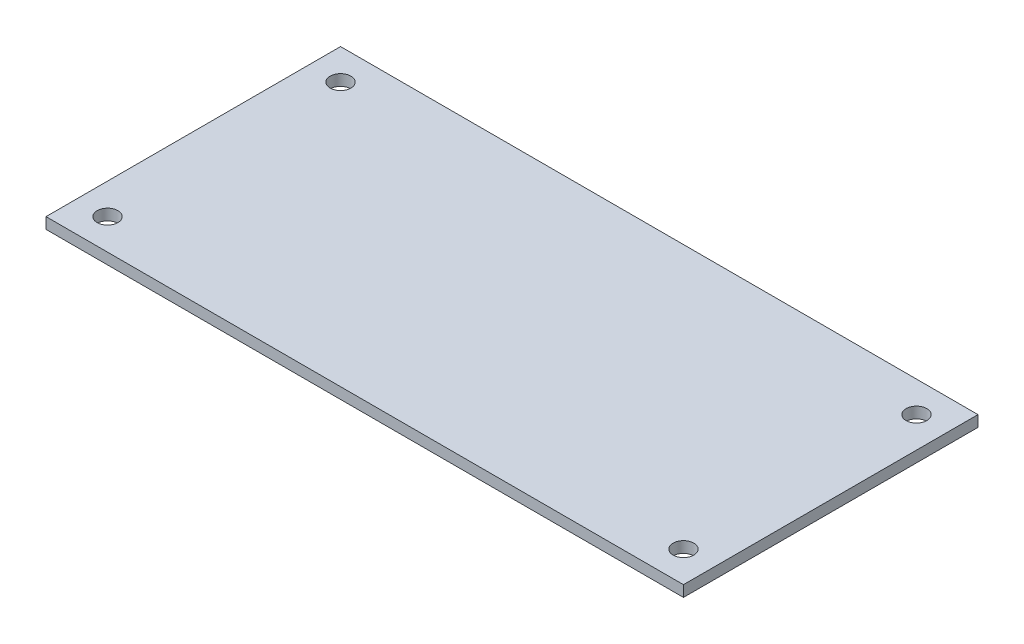
SolidWorks part; units mm, degrees
ref_plane "Front" through (0, 0, 0) normal (0, 0, 1) x (1, 0, 0)
ref_plane "Top" through (0, 0, 0) normal (0, 1, 0) x (1, 0, 0)
ref_plane "Right" through (0, 0, 0) normal (1, 0, 0) x (0, 0, -1)
sketch "Sketch2" plane through (0, 0, 0) normal (0, 1, 0) x (1, 0, 0)
  line L1 (-46.0375, 21.2725) -> (46.0375, 21.2725)
  line L2 (-46.0375, 21.2725) -> (-46.0375, -21.2725)
  line L3 (-46.0375, -21.2725) -> (46.0375, -21.2725)
  line L4 (46.0375, 21.2725) -> (46.0375, -21.2725)
  line L5 (-46.0375, 21.2725) -> (46.0375, -21.2725) construction
  line L6 (-46.0375, -21.2725) -> (46.0375, 21.2725) construction
  point P0 (0, 0)
  dimension "D1" = 42.545
  dimension "D2" = 92.075
extrude "PCBBase" add sketch "Sketch2" along normal blind 1.6
hole_wizard "Ø3.0mm Dowel Hole2" positions "Sketch6" profile "Sketch5" hole size "Ø3.0" standard "ANSI Metric" end condition through all
sketch "Sketch6" plane through (0, 0, 0) normal (0, 1, 0) x (1, 0, 0)
  line L0 (-46.0375, 21.2725) -> (-46.0375, -21.2725) construction
  line L1 (46.0375, 21.2725) -> (-46.0375, 21.2725) construction
  line L2 (-46.0375, -21.2725) -> (46.0375, -21.2725) construction
  line L4 (46.0375, -21.2725) -> (46.0375, 21.2725) construction
  point P0 (-41.5925, 16.8275)
  point P2 (-41.5925, -16.8275)
  point P4 (41.5925, -16.8275)
  point P6 (41.5925, 16.8275)
  dimension "D1" = 4.445
  dimension "D2" = 4.445
  dimension "D3" = 4.445
  dimension "D4" = 4.445
sketch "Sketch5" plane through (-41.5925, 0, -16.8275) normal (1, 0, 0) x (0, 0, -1)
  line L0 (0, 0) -> (0, 1.6)
  line L1 (0, 1.6) -> (1.5, 1.6)
  line L2 (1.5, 1.6) -> (1.5, 0)
  line L5 (1.5, 0) -> (0, 0)
  line L11 (0, -6.35) -> (0, 107.95) construction
  dimension "Thru Hole Dia." = 3
  dimension "Thru Hole Depth" = 1.6
